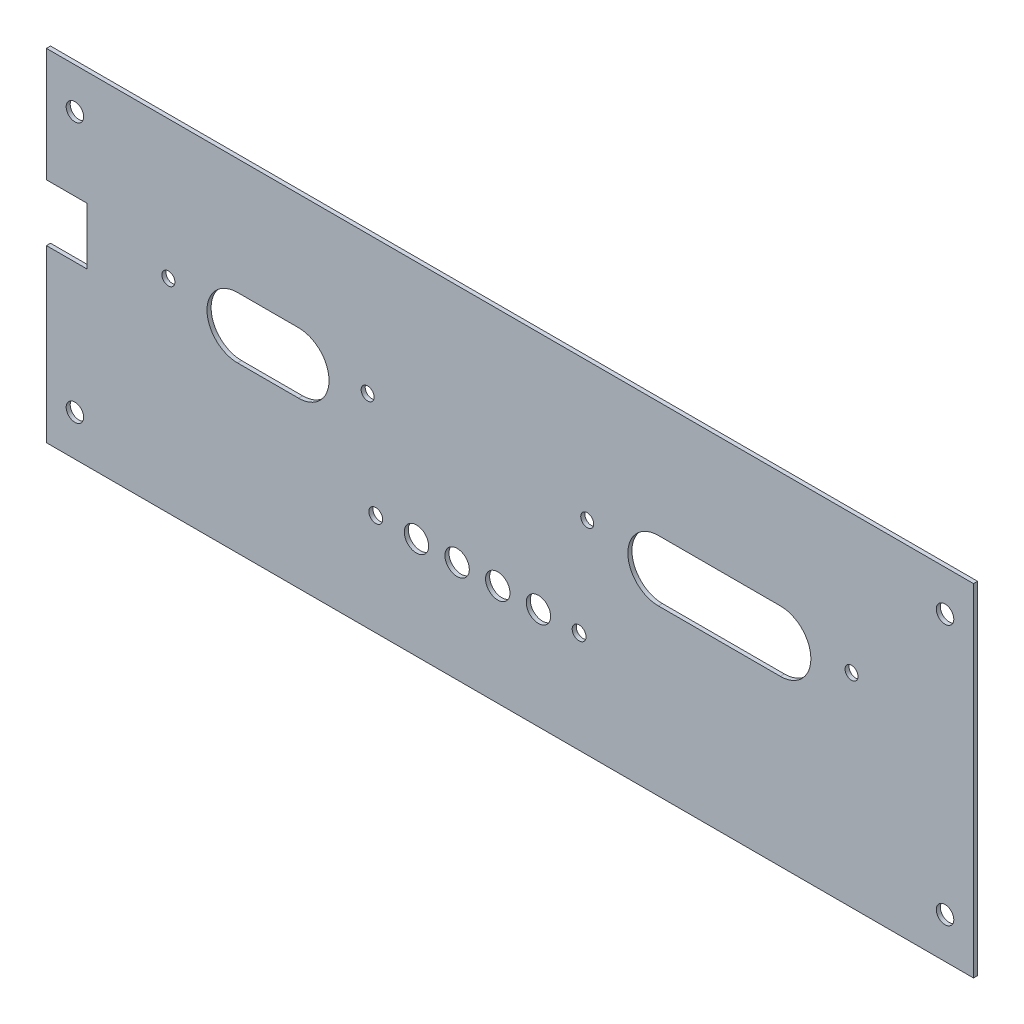
SolidWorks part; units mm, degrees
ref_plane "Спереди" through (0, 0, 0) normal (0, 0, 1) x (1, 0, 0)
ref_plane "Сверху" through (0, 0, 0) normal (0, 1, 0) x (1, 0, 0)
ref_plane "Справа" through (0, 0, 0) normal (1, 0, 0) x (0, 0, -1)
sketch "Эскиз1" plane through (0, 0, 0) normal (0, 0, 1) x (1, 0, 0)
  line L0 (0, 0) -> (58.061, 0) construction
  line L1 (0, 0) -> (0, 47.3035) construction
  line L3 (-114, -42) -> (114, -42)
  line L4 (-114, -42) -> (-114, 42)
  line L5 (-114, 42) -> (114, 42)
  line L6 (114, -42) -> (114, 42)
  circle A8 centre (107, 32) radius 2.15
  circle A9 centre (-107, 32) radius 2.15
  circle A10 centre (-107, -32) radius 2.15
  circle A11 centre (107, -32) radius 2.15
  dimension "D14" = 4.3
  dimension "D15" = 10
  dimension "D16" = 7
  dimension "D1" = 84
  dimension "D2" = 228
extrude "Вытянуть1" add sketch "Эскиз1" along normal blind 1
sketch "Эскиз4" plane through (0, 0, 1) normal (0, 0, 1) x (1, 0, 0)
  line L0 (-114, 42) -> (-114, -42) construction
  line L1 (-114, -42) -> (114, -42) construction
  line L2 (-95.842, 6) -> (24.8302, 6) construction
  line L3 (36.5, 13.5) -> (66.5, 13.5)
  line L4 (36.5, -1.5) -> (66.5, -1.5)
  line L5 (51.5, -2.1564) -> (51.5, -32.5755) construction
  line L6 (-67, 13.5) -> (-52, 13.5)
  line L7 (-67, -1.5) -> (-52, -1.5)
  line L8 (-59.5, -4.8658) -> (-59.5, -32.5755) construction
  line L9 (19, 8) -> (84, 8) construction
  line L10 (0, 76.9526) -> (0, -67.5216) construction
  line L11 (114, -42) -> (114, 42) construction
  line L13 (-118.4641, 0) -> (-104, 0)
  line L14 (-118.4641, 0) -> (-118.4641, 14)
  line L15 (-118.4641, 14) -> (-104, 14)
  line L16 (-104, 0) -> (-104, 14)
  arc A1 (36.5, 13.5) -> (36.5, -1.5) centre (36.5, 6) ccw
  arc A2 (66.5, 13.5) -> (66.5, -1.5) centre (66.5, 6) cw
  circle A3 centre (19, 8) radius 1.6
  circle A4 centre (84, 8) radius 1.6
  arc A5 (-67, 13.5) -> (-67, -1.5) centre (-67, 6) ccw
  arc A6 (-52, 13.5) -> (-52, -1.5) centre (-52, 6) cw
  circle A7 centre (-84, 8) radius 1.6
  circle A8 centre (-35, 8) radius 1.6
  dimension "D3" = 14
  dimension "D6" = 15
  dimension "D5" = 30
  dimension "D8" = 2
  dimension "D4" = 48
  dimension "D9" = 3.2
  dimension "D7" = 32.5
  dimension "D12" = 30
  dimension "D13" = 15
  dimension "D14" = 49
  dimension "D15" = 2
  dimension "D11" = 32.5
  dimension "D10" = 30
  dimension "D2" = 10
  dimension "D16" = 15
  dimension "D17" = 42
extrude "Вырез-Вытянуть2" cut sketch "Эскиз4" against normal blind 1
sketch "Эскиз5" plane through (0, 0, 1) normal (0, 0, 1) x (1, 0, 0)
  line L0 (-8, 37.0344) -> (-8, 0) construction
  line L1 (-33, -17) -> (17, -17) construction
  line L4 (-114, -42) -> (114, -42) construction
  circle A0 centre (-33, -17) radius 1.7
  circle A1 centre (17, -17) radius 1.7
  circle A2 centre (-35, 8) radius 1.6 construction
  circle A3 centre (19, 8) radius 1.6 construction
  circle A4 centre (7, -17) radius 3
  circle A5 centre (-3, -17) radius 3
  circle A6 centre (-13, -17) radius 3
  circle A7 centre (-23, -17) radius 3
  circle A10 centre (27, -17) radius 3 [skipped]
  circle A11 centre (-43, -17) radius 3 [skipped]
  circle A12 centre (17, -17) radius 3 [skipped]
  circle A13 centre (-33, -17) radius 3 [skipped]
  dimension "D1" = 50
  dimension "D2" = 3.4
  dimension "D5" = 30
  dimension "D6" = 6
  dimension "D3" = 25
extrude "Вырез-Вытянуть3" cut sketch "Эскиз5" against normal blind 10
